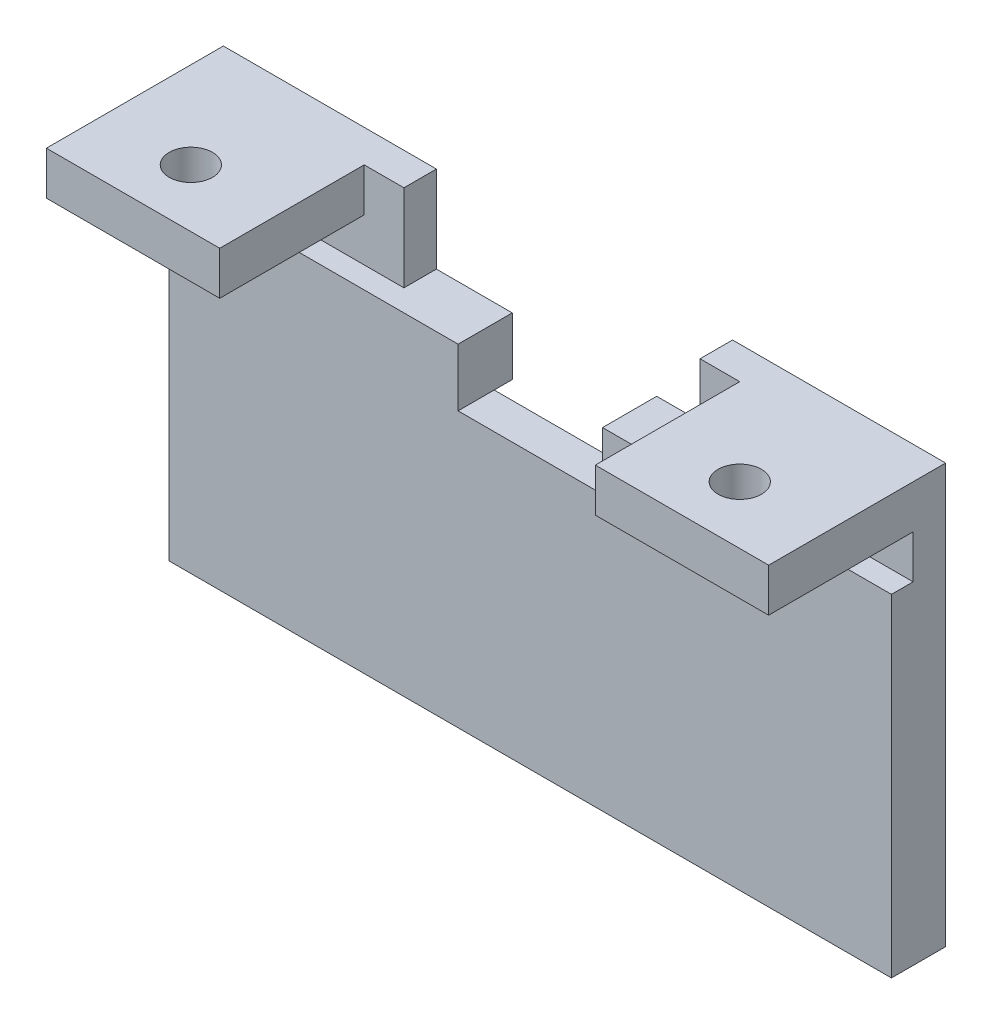
SolidWorks part; units mm, degrees
ref_plane "Front Plane" through (0, 0, 0) normal (0, 0, 1) x (1, 0, 0)
ref_plane "Top Plane" through (0, 0, 0) normal (0, 1, 0) x (1, 0, 0)
ref_plane "Right Plane" through (0, 0, 0) normal (1, 0, 0) x (0, 0, -1)
sketch "Sketch1" plane through (0, 0, 0) normal (0, 0, 1) x (1, 0, 0)
  line L1 (25, -11.5) -> (-25, -11.5)
  line L2 (25, -11.5) -> (25, 11.5)
  line L3 (10.25, 11.5) -> (-10.25, 11.5)
  line L4 (-25, -11.5) -> (-25, 11.5)
  line L5 (25, -11.5) -> (-25, 11.5) construction
  line L6 (25, 11.5) -> (-25, -11.5) construction
  line L8 (-25, 11.5) -> (-25, 17.5)
  line L9 (-25, 17.5) -> (-10.25, 17.5)
  line L10 (-10.25, 11.5) -> (-10.25, 17.5)
  line L12 (25, 11.5) -> (25, 17.5)
  line L13 (25, 17.5) -> (10.25, 17.5)
  line L14 (10.25, 11.5) -> (10.25, 17.5)
  point P0 (0, 0)
  dimension "D1" = 50
  dimension "D2" = 23
  dimension "D3" = 14.75
  dimension "D4" = 14.75
  dimension "D5" = 0
  dimension "D6" = 6
extrude "Boss-Extrude1" add sketch "Sketch1" along normal blind 2.25
sketch "Sketch2" plane through (0, 17.5, 0) normal (0, 1, 0) x (1, 0, 0)
  line L0 (25, -2.25) -> (25, 0) construction
  line L5 (13, -2.25) -> (25, -2.25)
  line L7 (13, -12.25) -> (25, -12.25)
  line L8 (25, -2.25) -> (25, -12.25)
  line L9 (0, 0) -> (0, -13.6621) construction
  line L10 (25, -2.25) -> (10.25, -2.25) construction
  line L11 (13, -12.25) -> (13, -2.25)
  line L12 (-13, -12.25) -> (-13, -2.25)
  line L13 (-25, -2.25) -> (-25, -12.25)
  line L14 (-13, -12.25) -> (-25, -12.25)
  line L15 (-13, -2.25) -> (-25, -2.25)
  circle A0 centre (19, -8.25) radius 1.5
  circle A1 centre (-19, -8.25) radius 1.5
  dimension "D2" = 3
  dimension "D1" = 0
  dimension "D3" = 2.75
  dimension "D4" = 4
  dimension "D5" = 6
  dimension "D6" = 6
extrude "Boss-Extrude3" add sketch "Sketch2" against normal blind 3
sketch "Sketch3" plane through (0, -11.5, 0) normal (0, -1, 0) x (1, 0, 0)
  line L7 (-25, 0) -> (25, 0) construction
  line L8 (-23, 0) -> (23, 0)
  line L9 (-23, 0) -> (-23, 1.25)
  line L10 (-23, 1.25) -> (23, 1.25)
  line L11 (23, 0) -> (23, 1.25)
  line L12 (-25, 2.25) -> (-25, 0) construction
  line L13 (25, 2.25) -> (25, 0) construction
  line L14 (-25, 2.25) -> (25, 2.25) construction
  line L15 (-16, 1.25) -> (-11, 1.25)
  line L16 (-16, 1.25) -> (-16, 2.25)
  line L17 (-16, 2.25) -> (-11, 2.25)
  line L18 (-11, 1.25) -> (-11, 2.25)
  line L19 (0, 0) -> (0, 2.25) construction
  line L20 (-13.5, 2.25) -> (-13.5, 1.25) construction
  line L21 (16, 2.25) -> (11, 2.25)
  line L22 (11, 1.25) -> (11, 2.25)
  line L23 (16, 1.25) -> (11, 1.25)
  line L24 (16, 1.25) -> (16, 2.25)
  line M3 (-25, 0) -> (25, 0)
  line M5 (25, 2.25) -> (-25, 2.25)
  dimension "D1" = 1.25
  dimension "D2" = 2
  dimension "D3" = 2
  dimension "D4" = 5
  dimension "D5" = 11.5
extrude "Cut-Extrude1" cut sketch "Sketch3" against normal offset from surface (19 mm away) 4 contours L11 L10 L9 M3 | L10 L18 L16 M5 | L10 L24 L22 M5 up to face at (0, 11.5, 1.125)
sketch "Sketch4" plane through (0, 0, 2.25) normal (0, 0, 1) x (1, 0, 0)
  line L0 (25, -11.5) -> (25, 14.5) construction
  line L1 (-25, -11.5) -> (25, -11.5)
  line L2 (-25, -11.5) -> (-25, 11.5)
  line L3 (-25, 11.5) -> (25, 11.5)
  line L4 (25, -11.5) -> (25, 11.5)
  line L5 (10.25, 11.5) -> (-10.25, 11.5) construction
  dimension "D1" = 0
extrude "Boss-Extrude5" add sketch "Sketch4" along normal blind 1.5
sketch "Sketch5" plane through (0, 11.5, 0) normal (0, 1, 0) x (1, 0, 0)
  line L0 (10.25, 0) -> (-10.25, 0) construction
  line L1 (5, -3.75) -> (-5, -3.75)
  line L2 (5, -3.75) -> (5, 0)
  line L3 (5, 0) -> (-5, 0)
  line L4 (-5, -3.75) -> (-5, 0)
  line L5 (5, -3.75) -> (-5, 0) construction
  line L6 (5, 0) -> (-5, -3.75) construction
  line L7 (25, -3.75) -> (-25, -3.75) construction
  line L9 (-10.25, -2.25) -> (-10.25, 0) construction
  point P0 (0, -1.875)
  dimension "D1" = 0
  dimension "D2" = 10
  dimension "D3" = 5.25
extrude "Cut-Extrude2" cut sketch "Sketch5" against normal blind 4
sketch "Sketch7" plane through (0, 0, 1.25) normal (0, 0, -1) x (-1, 0, 0)
  line L0 (0, 7.5) -> (0, -11.5) construction
  line L1 (5, 7.5) -> (-5, 7.5) construction
  line L2 (11, -11.5) -> (-11, -11.5) construction
  line L4 (-6, -9.5) -> (6, -9.5)
  line L5 (-6, -9.5) -> (-6, -11.5)
  line L6 (-6, -11.5) -> (6, -11.5)
  line L7 (6, -9.5) -> (6, -11.5)
  line L8 (-6, -9.5) -> (6, -11.5) construction
  line L9 (-6, -11.5) -> (6, -9.5) construction
  point P6 (0, -10.5)
  dimension "D1" = 2
  dimension "D2" = 12
extrude "Boss-Extrude6" add sketch "Sketch7" along normal blind 5
sketch "Sketch8" plane through (0, 0, 1.25) normal (0, 0, -1) x (-1, 0, 0)
  line L1 (23, -11.5) -> (6, -11.5)
  line L2 (23, -11.5) -> (23, -9.5)
  line L3 (23, -9.5) -> (6, -9.5)
  line L4 (6, -11.5) -> (6, -9.5)
  line L5 (-23, -11.5) -> (-6, -11.5)
  line L6 (-23, -11.5) -> (-23, -9.5)
  line L7 (-23, -9.5) -> (-6, -9.5)
  line L8 (-6, -11.5) -> (-6, -9.5)
extrude "Boss-Extrude7" add sketch "Sketch8" along normal up to surface and the other way up to surface
